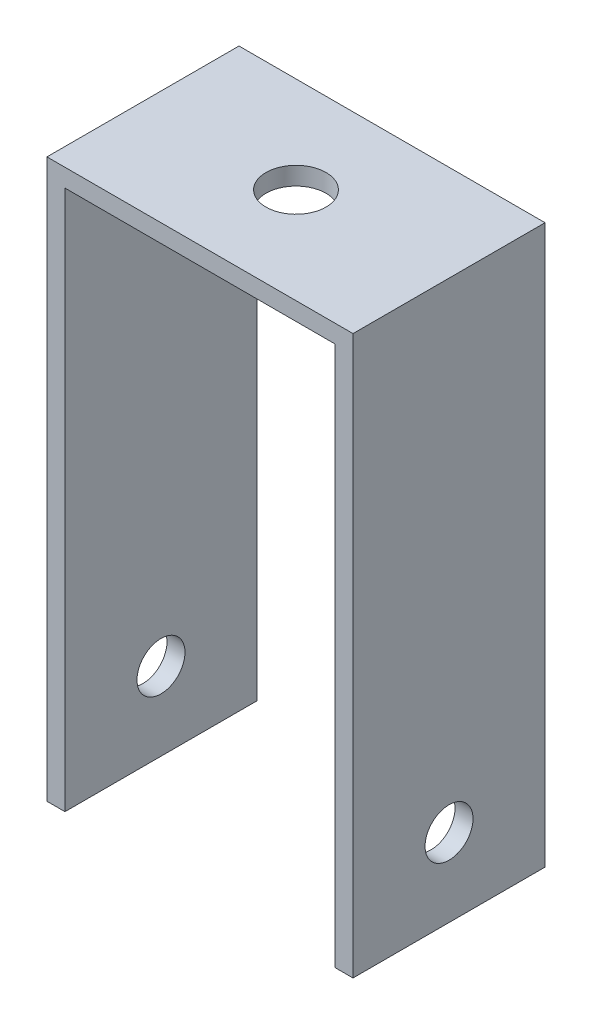
SolidWorks part; units mm, degrees
ref_plane "Front Plane" through (0, 0, 0) normal (0, 0, 1) x (1, 0, 0)
ref_plane "Top Plane" through (0, 0, 0) normal (0, 1, 0) x (1, 0, 0)
ref_plane "Right Plane" through (0, 0, 0) normal (1, 0, 0) x (0, 0, -1)
sketch "Sketch1" plane through (0, 0, 0) normal (0, 0, 1) x (1, 0, 0)
  line L0 (-25.5, 0) -> (25.5, 0)
  line L1 (0, -51.15) -> (0, 51.15) construction
  line L2 (0, 0) -> (0, -3) construction
  line L3 (-22.5, -3) -> (22.5, -3)
  line L4 (-22.5, -3) -> (-22.5, -93)
  line L5 (-25.5, 0) -> (-25.5, -93)
  line L6 (-25.5, -93) -> (-22.5, -93)
  line L7 (22.5, -3) -> (22.5, -93)
  line L8 (25.5, 0) -> (25.5, -93)
  line L9 (25.5, -93) -> (22.5, -93)
  point P6 (0, 0)
  dimension "D1" = 45
  dimension "D2" = 90
  dimension "D3" = 93
  dimension "D4" = 3
extrude "Boss-Extrude1" add sketch "Sketch1" along normal mid plane 32
sketch "Sketch2" plane through (25.5, 0, 0) normal (1, 0, 0) x (0, 0, -1)
  line L0 (-16, 0) -> (16, 0) construction
  line L1 (16, -93) -> (16, 0) construction
  circle A0 centre (0, -80) radius 4
  dimension "D1" = 8
  dimension "D2" = 80
  dimension "D3" = 16
extrude "Cut-Extrude1" cut sketch "Sketch2" against normal through all
sketch "Sketch3" plane through (0, 0, 0) normal (0, 1, 0) x (1, 0, 0)
  circle A0 centre (0, 0) radius 5
extrude "Cut-Extrude2" cut sketch "Sketch3" against normal blind 10
